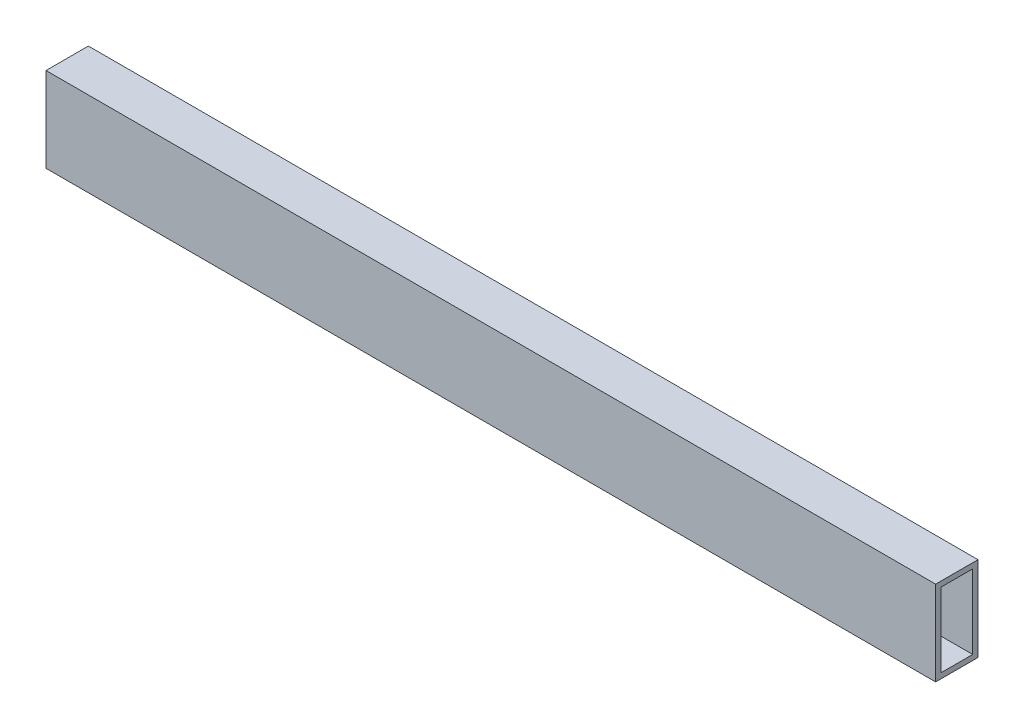
SolidWorks part; units mm, degrees
material "6061-T6 (SS)"
ref_plane "Front Plane" through (0, 0, 0) normal (0, 0, 1) x (1, 0, 0)
ref_plane "Top Plane" through (0, 0, 0) normal (0, 1, 0) x (1, 0, 0)
ref_plane "Right Plane" through (0, 0, 0) normal (1, 0, 0) x (0, 0, -1)
sketch "Sketch1" plane through (0, 0, 0) normal (1, 0, 0) x (0, 0, -1)
  line L0 (-330.2, 25.4) -> (-355.6, 25.4) construction
  line L1 (-355.6, -25.4) -> (-355.6, 25.4) construction
  line L2 (-330.2, -25.4) -> (-355.6, -25.4) construction
  line L3 (-330.2, -25.4) -> (-330.2, 25.4) construction
  line L4 (-330.2, 25.4) -> (-355.6, 25.4)
  line L5 (-355.6, -25.4) -> (-355.6, 25.4)
  line L6 (-330.2, -25.4) -> (-355.6, -25.4)
  line L7 (-330.2, -25.4) -> (-330.2, 25.4)
  line L8 (-333.375, 22.225) -> (-352.425, 22.225)
  line L9 (-352.425, -22.225) -> (-352.425, 22.225)
  line L10 (-333.375, -22.225) -> (-352.425, -22.225)
  line L11 (-333.375, -22.225) -> (-333.375, 22.225)
  dimension "D1" = 3.175
extrude "Boss-Extrude1" add sketch "Sketch1" along normal up to vertex (266.7 mm away)
mirror "Mirror1" about plane through (0, 0, 0) normal (1, 0, 0) of "Boss-Extrude1"
